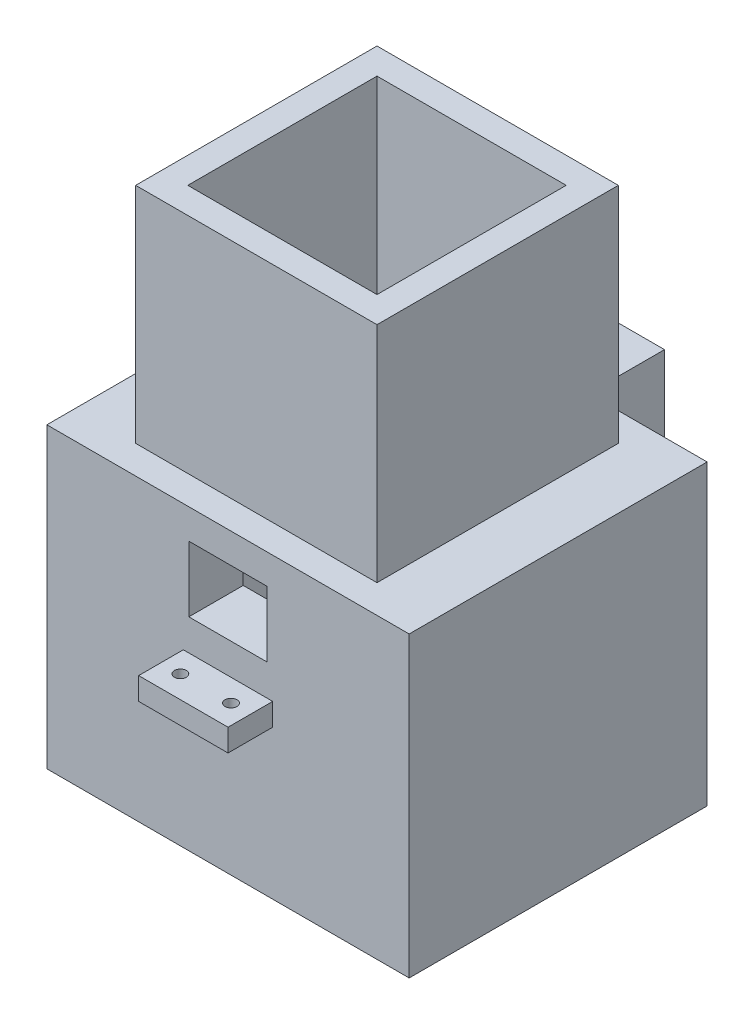
SolidWorks part; units mm, degrees
ref_plane "前基準面" through (0, 0, 0) normal (0, 0, 1) x (1, 0, 0)
ref_plane "上基準面" through (0, 0, 0) normal (0, 1, 0) x (1, 0, 0)
ref_plane "右基準面" through (0, 0, 0) normal (1, 0, 0) x (0, 0, -1)
sketch "草圖1" plane through (0, 0, 0) normal (0, 1, 0) x (1, 0, 0)
  line L1 (-12.16, 10) -> (12.16, 10)
  line L2 (-12.16, 10) -> (-12.16, -10)
  line L3 (-12.16, -10) -> (12.16, -10)
  line L4 (12.16, 10) -> (12.16, -10)
  line L5 (-12.16, 10) -> (12.16, -10) construction
  line L6 (-12.16, -10) -> (12.16, 10) construction
  line L7 (-10.46, 5.08) -> (-7.86, 5.08) construction
  line L8 (-10.46, 5.08) -> (-10.46, -5.08) construction
  line L9 (-10.46, -5.08) -> (-7.86, -5.08) construction
  line L10 (-7.86, 5.08) -> (-7.86, -5.08) construction
  line L11 (-8.1, 8.1) -> (8.1, 8.1)
  line L12 (-8.1, 8.1) -> (-8.1, -8.1)
  line L13 (-8.1, -8.1) -> (8.1, -8.1)
  line L14 (8.1, 8.1) -> (8.1, -8.1)
  line L15 (-8.1, 8.1) -> (8.1, -8.1) construction
  line L16 (-8.1, -8.1) -> (8.1, 8.1) construction
  line L17 (-6.35, 6.35) -> (6.35, 6.35)
  line L18 (-6.35, 6.35) -> (-6.35, -6.35)
  line L19 (-6.35, -6.35) -> (6.35, -6.35)
  line L20 (6.35, 6.35) -> (6.35, -6.35)
  line L21 (-6.35, 6.35) -> (6.35, -6.35) construction
  line L22 (-6.35, -6.35) -> (6.35, 6.35) construction
  point P0 (0, 0)
  point P10 (-9.16, 5.08)
  point P11 (0, 0)
  point P17 (0, 0)
  dimension "D1" = 24.32
  dimension "D2" = 20
  dimension "D3" = 2.6
  dimension "D4" = 10.16
  dimension "D5" = 4.92
  dimension "D6" = 1.7
  dimension "D7" = 16.2
  dimension "D8" = 16.2
  dimension "D9" = 12.7
  dimension "D10" = 12.7
extrude "填料-伸長1" add sketch "草圖1" along normal blind 35 contours L14 L11 L12 L13 L17 L20 L19 L18
sketch "草圖3" plane through (0, 0, 0) normal (0, 1, 0) x (1, 0, 0)
  line L1 (-12.16, 10) -> (12.16, 10)
  line L2 (-12.16, 10) -> (-12.16, -10)
  line L3 (-12.16, -10) -> (12.16, -10)
  line L4 (12.16, 10) -> (12.16, -10)
  line L5 (-12.16, 10) -> (12.16, -10) construction
  line L6 (-12.16, -10) -> (12.16, 10) construction
  line L7 (-10.46, 5.08) -> (-7.86, 5.08) construction
  line L8 (-10.46, 5.08) -> (-10.46, -5.08) construction
  line L9 (-10.46, -5.08) -> (-7.86, -5.08) construction
  line L10 (-7.86, 5.08) -> (-7.86, -5.08) construction
  line L11 (-7.35, 7.35) -> (7.35, 7.35)
  line L12 (-7.35, 7.35) -> (-7.35, -7.35)
  line L13 (-7.35, -7.35) -> (7.35, -7.35)
  line L14 (7.35, 7.35) -> (7.35, -7.35)
  line L15 (-7.35, 7.35) -> (7.35, -7.35) construction
  line L16 (-7.35, -7.35) -> (7.35, 7.35) construction
  line L17 (-6.35, 6.35) -> (6.35, 6.35)
  line L18 (-6.35, 6.35) -> (-6.35, -6.35)
  line L19 (-6.35, -6.35) -> (6.35, -6.35)
  line L20 (6.35, 6.35) -> (6.35, -6.35)
  line L21 (-6.35, 6.35) -> (6.35, -6.35) construction
  line L22 (-6.35, -6.35) -> (6.35, 6.35) construction
  point P0 (0, 0)
  point P10 (-9.16, 5.08)
  point P11 (0, 0)
  point P17 (0, 0)
  dimension "D1" = 24.32
  dimension "D2" = 20
  dimension "D3" = 2.6
  dimension "D4" = 10.16
  dimension "D5" = 4.92
  dimension "D6" = 1.7
  dimension "D7" = 14.7
  dimension "D8" = 14.7
  dimension "D9" = 12.7
  dimension "D10" = 12.7
extrude "填料-伸長2" add sketch "草圖3" along normal blind 1 separate body contours L20 L17 L18 L19
sketch "草圖5" plane through (0, 0, 0) normal (0, 1, 0) x (1, 0, 0)
  line L0 (0, 10) -> (0, -10.2763) construction
  line L1 (-12.16, 10) -> (12.16, 10)
  line L2 (-12.16, 10) -> (-12.16, -10)
  line L3 (-12.16, -10) -> (12.16, -10)
  line L4 (12.16, 10) -> (12.16, -10)
  line L5 (-12.16, 10) -> (12.16, -10) construction
  line L6 (-12.16, -10) -> (12.16, 10) construction
  line L7 (-10.46, 5.08) -> (-7.86, 5.08)
  line L8 (-10.46, 5.08) -> (-10.46, -5.08)
  line L9 (-10.46, -5.08) -> (-7.86, -5.08)
  line L10 (-7.86, 5.08) -> (-7.86, -5.08)
  line L11 (-7.35, 7.35) -> (7.35, 7.35)
  line L12 (-7.35, 7.35) -> (-7.35, -7.35)
  line L13 (-7.35, -7.35) -> (7.35, -7.35)
  line L14 (7.35, 7.35) -> (7.35, -7.35)
  line L15 (-7.35, 7.35) -> (7.35, -7.35) construction
  line L16 (-7.35, -7.35) -> (7.35, 7.35) construction
  line L17 (-6.35, 6.35) -> (6.35, 6.35)
  line L18 (-6.35, 6.35) -> (-6.35, -6.35)
  line L19 (-6.35, -6.35) -> (6.35, -6.35)
  line L20 (6.35, 6.35) -> (6.35, -6.35)
  line L21 (-6.35, 6.35) -> (6.35, -6.35) construction
  line L22 (-6.35, -6.35) -> (6.35, 6.35) construction
  line L23 (10.46, -5.08) -> (7.86, -5.08)
  line L24 (7.86, 5.08) -> (7.86, -5.08)
  line L25 (10.46, 5.08) -> (7.86, 5.08)
  line L26 (10.46, 5.08) -> (10.46, -5.08)
  point P0 (0, 0)
  point P10 (-9.16, 5.08)
  point P11 (0, 0)
  point P17 (0, 0)
  dimension "D1" = 24.32
  dimension "D2" = 20
  dimension "D3" = 2.6
  dimension "D4" = 10.16
  dimension "D5" = 4.92
  dimension "D6" = 1.7
  dimension "D7" = 14.7
  dimension "D8" = 14.7
  dimension "D9" = 12.7
  dimension "D10" = 12.7
extrude "填料-伸長3" add sketch "草圖5" along normal blind 20 contours L4 L1 L2 L3 L7 L10 L9 L8 L11 L14 L13 L12 L25 L26 L23 L24 | L10 L7 L8 L9 | L26 L25 L24 L23
sketch "草圖6" plane through (0, 0, 0) normal (0, 1, 0) x (1, 0, 0)
  line L1 (-12.16, 10) -> (12.16, 10)
  line L2 (-12.16, 10) -> (-12.16, -10)
  line L3 (-12.16, -10) -> (12.16, -10)
  line L4 (12.16, 10) -> (12.16, -10)
  line L5 (-12.16, 10) -> (12.16, -10) construction
  line L6 (-12.16, -10) -> (12.16, 10) construction
  line L7 (-10.46, 5.08) -> (-7.86, 5.08) construction
  line L8 (-10.46, 5.08) -> (-10.46, -5.08) construction
  line L9 (-10.46, -5.08) -> (-7.86, -5.08) construction
  line L10 (-7.86, 5.08) -> (-7.86, -5.08) construction
  line L11 (-7.35, 7.35) -> (7.35, 7.35)
  line L12 (-7.35, 7.35) -> (-7.35, -7.35)
  line L13 (-7.35, -7.35) -> (7.35, -7.35)
  line L14 (7.35, 7.35) -> (7.35, -7.35)
  line L15 (-7.35, 7.35) -> (7.35, -7.35) construction
  line L16 (-7.35, -7.35) -> (7.35, 7.35) construction
  line L17 (-6.35, 6.35) -> (6.35, 6.35)
  line L18 (-6.35, 6.35) -> (-6.35, -6.35)
  line L19 (-6.35, -6.35) -> (6.35, -6.35)
  line L20 (6.35, 6.35) -> (6.35, -6.35)
  line L21 (-6.35, 6.35) -> (6.35, -6.35) construction
  line L22 (-6.35, -6.35) -> (6.35, 6.35) construction
  point P0 (0, 0)
  point P10 (-9.16, 5.08)
  point P11 (0, 0)
  point P17 (0, 0)
  dimension "D1" = 24.32
  dimension "D2" = 20
  dimension "D3" = 2.6
  dimension "D4" = 10.16
  dimension "D5" = 4.92
  dimension "D6" = 1.7
  dimension "D7" = 14.7
  dimension "D8" = 14.7
  dimension "D9" = 12.7
  dimension "D10" = 12.7
sketch "草圖8" plane through (0, 0, 0) normal (0, -1, 0) x (1, 0, 0)
  line L0 (0, 10) -> (0, -10.2763) construction
  line L1 (-12.16, 10) -> (12.16, 10)
  line L2 (-12.16, 10) -> (-12.16, -10)
  line L3 (-12.16, -10) -> (12.16, -10)
  line L4 (12.16, 10) -> (12.16, -10)
  line L5 (-12.16, 10) -> (12.16, -10) construction
  line L6 (-12.16, -10) -> (12.16, 10) construction
  line L7 (-10.46, 5.08) -> (-7.86, 5.08)
  line L8 (-10.46, 5.08) -> (-10.46, -5.08)
  line L9 (-10.46, -5.08) -> (-7.86, -5.08)
  line L10 (-7.86, 5.08) -> (-7.86, -5.08)
  line L11 (-7.35, 7.35) -> (7.35, 7.35)
  line L12 (-7.35, 7.35) -> (-7.35, -7.35)
  line L13 (-7.35, -7.35) -> (7.35, -7.35)
  line L14 (7.35, 7.35) -> (7.35, -7.35)
  line L15 (-7.35, 7.35) -> (7.35, -7.35) construction
  line L16 (-7.35, -7.35) -> (7.35, 7.35) construction
  line L17 (-6.35, 6.35) -> (6.35, 6.35)
  line L18 (-6.35, 6.35) -> (-6.35, -6.35)
  line L19 (-6.35, -6.35) -> (6.35, -6.35)
  line L20 (6.35, 6.35) -> (6.35, -6.35)
  line L21 (-6.35, 6.35) -> (6.35, -6.35) construction
  line L22 (-6.35, -6.35) -> (6.35, 6.35) construction
  line L23 (10.46, -5.08) -> (7.86, -5.08)
  line L24 (7.86, 5.08) -> (7.86, -5.08)
  line L25 (10.46, 5.08) -> (7.86, 5.08)
  line L26 (10.46, 5.08) -> (10.46, -5.08)
  point P0 (0, 0)
  point P10 (-9.16, 5.08)
  point P11 (0, 0)
  point P17 (0, 0)
  dimension "D1" = 24.32
  dimension "D2" = 20
  dimension "D3" = 2.6
  dimension "D4" = 10.16
  dimension "D5" = 4.92
  dimension "D6" = 1.7
  dimension "D7" = 14.7
  dimension "D8" = 14.7
  dimension "D9" = 12.7
  dimension "D10" = 12.7
sketch "草圖9" plane through (0, 0, 0) normal (0, 1, 0) x (1, 0, 0)
  line L0 (0, 10) -> (0, -10.2763) construction
  line L1 (-12.16, 10) -> (12.16, 10)
  line L2 (-12.16, 10) -> (-12.16, -10)
  line L3 (-12.16, -10) -> (12.16, -10)
  line L4 (12.16, 10) -> (12.16, -10)
  line L5 (-12.16, 10) -> (12.16, -10) construction
  line L6 (-12.16, -10) -> (12.16, 10) construction
  line L7 (-10.26, 5.3) -> (-7.52, 5.3)
  line L8 (-10.26, 5.3) -> (-10.26, -5.3)
  line L9 (-10.26, -5.3) -> (-7.52, -5.3)
  line L10 (-7.52, 5.3) -> (-7.52, -5.3)
  line L11 (-7.35, 7.35) -> (7.35, 7.35)
  line L12 (-7.35, 7.35) -> (-7.35, -7.35)
  line L13 (-7.35, -7.35) -> (7.35, -7.35)
  line L14 (7.35, 7.35) -> (7.35, -7.35)
  line L15 (-7.35, 7.35) -> (7.35, -7.35) construction
  line L16 (-7.35, -7.35) -> (7.35, 7.35) construction
  line L17 (-6.35, 6.35) -> (6.35, 6.35)
  line L18 (-6.35, 6.35) -> (-6.35, -6.35)
  line L19 (-6.35, -6.35) -> (6.35, -6.35)
  line L20 (6.35, 6.35) -> (6.35, -6.35)
  line L21 (-6.35, 6.35) -> (6.35, -6.35) construction
  line L22 (-6.35, -6.35) -> (6.35, 6.35) construction
  line L23 (10.26, -5.3) -> (7.52, -5.3)
  line L24 (7.52, 5.3) -> (7.52, -5.3)
  line L25 (10.26, 5.3) -> (7.52, 5.3)
  line L26 (10.26, 5.3) -> (10.26, -5.3)
  line L27 (-8.89, -5.3) -> (-8.89, 5.3) construction
  line L28 (8.89, -5.3) -> (8.89, 4.7757) construction
  line L29 (8.89, 4.7757) -> (8.89, 5.3) construction
  point P0 (0, 0)
  point P10 (-8.89, 5.3)
  point P11 (0, 0)
  point P17 (0, 0)
  dimension "D1" = 24.32
  dimension "D2" = 20
  dimension "D3" = 2.74
  dimension "D4" = 10.6
  dimension "D5" = 4.7
  dimension "D6" = 1.9
  dimension "D7" = 14.7
  dimension "D8" = 14.7
  dimension "D9" = 12.7
  dimension "D10" = 12.7
  dimension "D11" = 17.78
extrude "除料-伸長5" cut sketch "草圖9" along normal blind 8.7 contours L10 L7 L8 L9 | L26 L25 L24 L23
sketch "草圖10" plane through (0, 0, 10) normal (0, 0, 1) x (1, 0, 0)
  line L1 (-2.63, 18) -> (2.63, 18)
  line L2 (-2.63, 18) -> (-2.63, 13.6)
  line L3 (-2.63, 13.6) -> (2.63, 13.6)
  line L4 (2.63, 18) -> (2.63, 13.6)
  line L5 (-12.16, 20) -> (-12.16, 0) construction
  line L6 (-12.16, 0) -> (12.16, 0) construction
  dimension "D1" = 5.26
  dimension "D2" = 4.4
  dimension "D3" = 9.53
  dimension "D4" = 13.6
extrude "除料-伸長6" cut sketch "草圖10" against normal up to next
sketch "草圖12" plane through (0, 0, 10) normal (0, 0, 1) x (1, 0, 0)
  line L0 (-12.16, 10) -> (12.16, 10) construction
  line L1 (-12.16, 20) -> (-12.16, 0) construction
  line L2 (12.16, 20) -> (12.16, 0) construction
  line L3 (-12.16, 0) -> (12.16, 0) construction
  dimension "D1" = 10
ref_plane "平面1" through (0, 10, 0) normal (0, 1, 0) x (1, 0, 0)
sketch "草圖11" plane through (0, 10, 0) normal (0, 1, 0) x (1, 0, 0)
  line L0 (-12.16, -10) -> (12.16, -10) construction
  line L1 (-3, -10) -> (3, -10)
  line L2 (-3, -10) -> (-3, -13)
  line L3 (-3, -13) -> (3, -13)
  line L4 (3, -10) -> (3, -13)
  line L5 (0, -10) -> (0, -13) construction
  line L6 (12.16, 10) -> (12.16, -10) construction
  line L7 (-12.16, 10) -> (-12.16, -10) construction
  circle A0 centre (-1.7, -11.5) radius 0.4
  circle A1 centre (1.7, -11.5) radius 0.4
  dimension "D3" = 0.8
  dimension "D7" = 3.4
  dimension "D1" = 6
  dimension "D2" = 3
  dimension "D5" = 1.5
  dimension "D6" = 1.5
  dimension "D8" = 1.3
extrude "填料-伸長5" add sketch "草圖11" along normal blind 1.5
sketch "草圖13" plane through (0, 0, -10) normal (0, 0, -1) x (-1, 0, 0)
  line L0 (0, 18.6) -> (0, 13) construction
  line L1 (-2.8, 18.6) -> (2.8, 18.6)
  line L2 (-2.8, 18.6) -> (-2.8, 13)
  line L3 (-2.8, 13) -> (2.8, 13)
  line L4 (2.8, 18.6) -> (2.8, 13)
  line L5 (12.16, 20) -> (12.16, 0) construction
  line L6 (-12.16, 20) -> (-12.16, 0) construction
  line L7 (-4.2, 20) -> (-4.2, 11.6)
  line L8 (-4.2, 11.6) -> (4.2, 11.6)
  line L9 (4.2, 20) -> (4.2, 11.6)
  line L10 (-4.2, 20) -> (4.2, 20)
  line L11 (12.16, 20) -> (-12.16, 20) construction
  dimension "D1" = 5.6
  dimension "D2" = 5.6
  dimension "D4" = 1.4
  dimension "D3" = 1.4
extrude "填料-伸長6" add sketch "草圖13" along normal blind 5.1
sketch "草圖15" plane through (0, 0, -10) normal (0, 0, -1) x (-1, 0, 0)
  line L1 (-2.8, 18.6) -> (2.8, 18.6) construction
  line L2 (-2.8, 18.6) -> (-2.8, 13) construction
  line L3 (-2.8, 13) -> (2.8, 13) construction
  line L4 (2.8, 18.6) -> (2.8, 13) construction
  circle A0 centre (0, 15.8) radius 2.65
  dimension "D1" = 5.3
extrude "除料-伸長7" cut sketch "草圖15" against normal up to next
sketch "草圖16" plane through (0, 0, -10) normal (0, 0, -1) x (-1, 0, 0)
  line L0 (12.16, 0) -> (-12.16, 0) construction
  line L1 (-4.2, 10.6) -> (4.2, 10.6)
  line L2 (-4.2, 10.6) -> (-4.2, 9)
  line L3 (-4.2, 9) -> (4.2, 9)
  line L4 (4.2, 10.6) -> (4.2, 9)
  line L5 (0, 10.6) -> (0, 9) construction
  line L7 (12.16, 20) -> (12.16, 0) construction
  line L8 (-12.16, 20) -> (-12.16, 0) construction
  dimension "D1" = 8.4
  dimension "D2" = 1.6
  dimension "D3" = 9
extrude "填料-伸長7" add sketch "草圖16" along normal blind 7.4
sketch "草圖17" plane through (0, 10.6, 0) normal (0, 1, 0) x (1, 0, 0)
  line L0 (-4.2, 17.4) -> (4.2, 17.4) construction
  line L1 (4.2, 17.4) -> (4.2, 10) construction
  circle A0 centre (1.27, 16.15) radius 0.4
  circle A1 centre (-1.27, 16.15) radius 0.4
  dimension "D1" = 0.8
  dimension "D2" = 0.8
  dimension "D3" = 1.25
  dimension "D4" = 1.25
  dimension "D5" = 2.54
  dimension "D6" = 2.93
extrude "除料-伸長8" cut sketch "草圖17" against normal up to next
sketch "草圖18" plane through (0, 35, 0) normal (0, 1, 0) x (1, 0, 0)
sketch "草圖20" plane through (0, 0, -10) normal (0, 0, -1) x (-1, 0, 0)
  line L1 (-2.8, 18.6) -> (2.8, 18.6)
  line L2 (-2.8, 18.6) -> (-2.8, 13)
  line L3 (-2.8, 13) -> (2.8, 13)
  line L4 (2.8, 18.6) -> (2.8, 13)
  line L5 (-2.8, 18.6) -> (2.8, 13) construction
  line L6 (-2.8, 13) -> (2.8, 18.6) construction
  circle A0 centre (0, 15.8) radius 2.65
  dimension "D1" = 5.3
  dimension "D2" = 5.6
  dimension "D3" = 5.6
extrude "填料-伸長8" add sketch "草圖20" along normal blind 3.7
sketch "草圖21" plane through (0, 0, -10) normal (0, 0, -1) x (-1, 0, 0)
  line L0 (-4.2, 11.6) -> (4.2, 11.6) construction
  line L1 (-4.2, 10.6) -> (4.2, 10.6)
  line L2 (-4.2, 10.6) -> (-4.2, 11.6)
  line L3 (-4.2, 11.6) -> (4.2, 11.6)
  line L4 (4.2, 10.6) -> (4.2, 11.6)
  dimension "D1" = 8.4
extrude "填料-伸長9" add sketch "草圖21" along normal blind 5.1
